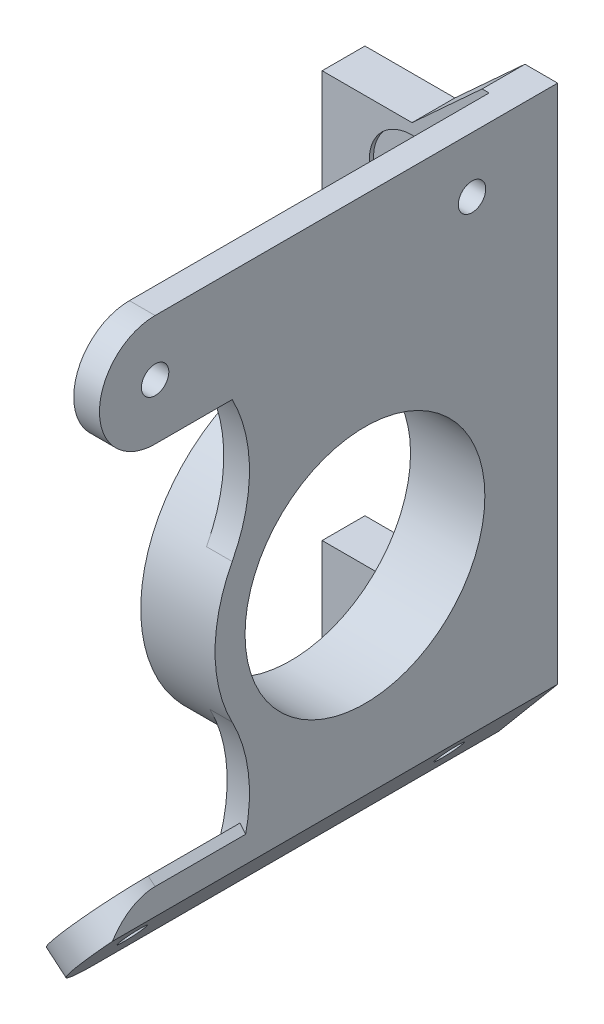
SolidWorks part; units mm, degrees
ref_plane "前视基准面" through (0, 0, 0) normal (0, 0, 1) x (1, 0, 0)
ref_plane "上视基准面" through (0, 0, 0) normal (0, 1, 0) x (1, 0, 0)
ref_plane "右视基准面" through (0, 0, 0) normal (1, 0, 0) x (0, 0, -1)
sketch "草图2" plane through (0, 0, 0) normal (0, 0, 1) x (1, 0, 0)
  line L0 (-14.7736, 24.3382) -> (-14.7736, -35.6618)
  line L1 (-14.7736, -35.6618) -> (30.2264, -35.6618)
  line L2 (7.7264, -35.6618) -> (7.7264, -23.1618)
  line L3 (21.55, -23.1618) -> (-6.0971, -23.1618)
  line L4 (-6.0971, -23.1618) -> (-6.0971, 11.8382)
  line L5 (-6.0971, 11.8382) -> (21.55, 11.8382)
  line L6 (7.7264, 11.8382) -> (7.7264, 24.3382)
  line L7 (30.2264, 24.3382) -> (-14.7736, 24.3382)
  line L8 (7.7264, 28.8603) -> (7.7264, -39.8897) construction
  line L9 (21.55, -23.1618) -> (21.55, 11.8382)
  line L10 (30.2264, 24.3382) -> (30.2264, -35.6618)
  line L11 (-18.1559, -5.6618) -> (33.2411, -5.6618) construction
  point P16 (-6.0971, -5.6618)
  point P17 (-14.7736, -5.6618)
  dimension "D1" = 45
  dimension "D2" = 35
  dimension "D3" = 60
extrude "凸台-拉伸2" add sketch "草图2" along normal blind 5 contours L6 L7 L0 L1 L2 L3 L4 L5 | L10 L7 L6 L5 L9 L3 L2 L1
sketch "草图4" plane through (0, 0, 5) normal (0, 0, 1) x (1, 0, 0)
  line L0 (-18.165, -5.6618) -> (33.9165, -5.6618) construction
  line L1 (-14.7736, 24.3382) -> (-14.7736, -35.6618) construction
  line L2 (-14.7736, -23.1618) -> (-6.0971, -23.1618)
  line L3 (-14.7736, -23.1618) -> (-14.7736, 11.8382)
  line L4 (-14.7736, 11.8382) -> (-6.0971, 11.8382)
  line L5 (-6.0971, -23.1618) -> (-6.0971, 11.8382)
  line L6 (-6.0971, -23.1618) -> (-6.0971, 11.8382) construction
  line L7 (7.7264, -39.813) -> (7.7264, 28.1228) construction
  line L8 (30.2264, 11.8382) -> (21.55, 11.8382)
  line L9 (21.55, -23.1618) -> (21.55, 11.8382)
  line L10 (30.2264, -23.1618) -> (21.55, -23.1618)
  line L11 (30.2264, -23.1618) -> (30.2264, 11.8382)
  point P17 (-14.7736, -5.6618)
  dimension "D1" = 35
extrude "凸台-拉伸15" add sketch "草图4" along normal blind 35
sketch "草图5" plane through (-14.7736, 0, 0) normal (-1, 0, 0) x (0, 0, 1)
  line L0 (0, -5.6618) -> (40, -5.6618)
  line L1 (0, 24.3382) -> (0, -35.6618) construction
  line L2 (40, 11.8382) -> (40, -23.1618) construction
  line L3 (22.5, 11.8382) -> (40, 11.8382)
  line L4 (40, 11.8382) -> (40, -23.1618)
  line L5 (40, -23.1618) -> (22.5, -23.1618)
  circle A0 centre (22.5, -5.6618) radius 17.5
  line M5 (5, -23.1618) -> (40, -23.1618)
  line M6 (40, -23.1618) -> (40, 11.8382)
  line M7 (40, 11.8382) -> (5, 11.8382)
  dimension "D1" = 35
extrude "切除-拉伸1" cut sketch "草图5" against normal blind 45 contours A0 M5 M6 | A0 M6 M7
sketch "草图6" plane through (-14.7736, 0, 0) normal (-1, 0, 0) x (0, 0, 1)
  circle A0 centre (22.5, -5.6618) radius 14
  dimension "D1" = 28
extrude "切除-拉伸2" cut sketch "草图6" against normal blind 45
fillet "圆角1" radius 5 4 edges at (-6.0971, 11.8382, 2.5) (21.55, 11.8382, 2.5) (-6.0971, -23.1618, 2.5) (21.55, -23.1618, 2.5)
sketch "草图7" plane through (-6.0971, 0, 0) normal (1, 0, 0) x (0, 0, -1)
  circle A0 centre (-22.5, -5.6618) radius 15
  circle A1 centre (-22.5, -5.6618) radius 13
extrude "凸台-拉伸16" add sketch "草图7" against normal blind 1
sketch "草图8" plane through (21.55, 0, 0) normal (-1, 0, 0) x (0, 0, 1)
  circle A0 centre (22.5, -5.6618) radius 15
  circle A1 centre (22.5, -5.6618) radius 10
sketch "草图9" plane through (0, 0, 5) normal (0, 0, 1) x (1, 0, 0)
  line L0 (7.7264, 24.3382) -> (7.7264, -35.6618)
  line L13 (30.2264, 24.3382) -> (-14.7736, 24.3382) construction
  line L14 (-14.7736, -35.6618) -> (30.2264, -35.6618) construction
sketch "草图11" plane through (0, 0, 5) normal (0, 0, 1) x (1, 0, 0)
  line L0 (-14.7736, 18.0882) -> (30.2264, 18.0882)
  line L1 (-14.7736, 24.3382) -> (-14.7736, 11.8382) construction
  line L2 (30.2264, 24.3382) -> (30.2264, 11.8382) construction
  line L3 (7.7264, 24.3382) -> (7.7264, -35.6618) construction
  line L4 (30.2264, 24.3382) -> (-14.7736, 24.3382) construction
  line L5 (-14.7736, -35.6618) -> (30.2264, -35.6618) construction
  line L6 (7.7264, -5.6618) -> (45.6912, -5.6618) construction
  line L7 (45.6912, -5.6618) -> (45.6912, 4.9969) construction
  line L10 (-14.7736, -29.4118) -> (30.2264, -29.4118)
  line L11 (-14.7736, -23.1618) -> (-14.7736, -35.6618) construction
  point P4 (-2.7736, 18.0882)
  point P16 (-2.7736, -29.4118)
  point P18 (18.2264, -29.4118)
  point P25 (18.2264, 18.0882)
  dimension "D1" = 12
split "分割1" trim tools "草图9" bodies to split 111 resulting bodies 117 118
delete or keep bodies "实体-删除/保留 2" type delete bodies bodies 117
hole_wizard "打孔尺寸(%根据六角头螺)栓 全螺纹的类型1" positions "3D草图2" profile "草图31" counterbore size "M4" standard "GB"
sketch3d "3D草图2"
  point P0 (18.2264, 18.0882, 5)
  point P3 (18.2264, -29.4118, 5)
sketch "草图31" plane through (18.2264, 18.0882, 5) normal (1, 0, 0) x (0, -1, 0)
  line L0 (0, 0) -> (0, 6.2919)
  line L1 (0, 6.2919) -> (2.15, 5)
  line L2 (2.15, 5) -> (2.15, 0.5)
  line L3 (2.15, 0.5) -> (5, 0.5)
  line L4 (5, 0.5) -> (5, 0)
  line L5 (5, 0) -> (0, 0)
  line L10 (0, 6.2919) -> (-2.15, 5) construction
  line L11 (0, -6.35) -> (0, 107.95) construction
  dimension "孔直径" = 4.3
  dimension "孔深度" = 5
  dimension "柱形沉头孔直径" = 10
  dimension "柱形沉头孔深度" = 0.5
  dimension "导头角度" = 118
sketch "草图17" plane through (0, 0, 5) normal (0, 0, 1) x (1, 0, 0)
  line L5 (30.2264, 31.8382) -> (27.2264, 31.8382)
  line L6 (30.2264, 31.8382) -> (30.2264, 18.8382)
  line L7 (30.2264, 18.8382) -> (27.2264, 18.8382)
  line L8 (27.2264, 31.8382) -> (27.2264, 18.8382)
  line L9 (30.2264, 24.3382) -> (30.2264, 11.8382) construction
  line L10 (30.2264, 11.8382) -> (21.55, 11.8382) construction
  dimension "D1" = 3
  dimension "D4" = 13
  dimension "D6" = 7
extrude "凸台-拉伸20" add sketch "草图17" along normal blind 42
sketch "草图18" plane through (30.2264, 0, 0) normal (1, 0, 0) x (0, 0, -1)
  line L3 (-47, 18.8382) -> (-47, 31.8382)
  arc A0 (-47, 31.8382) -> (-47, 18.8382) centre (-47, 25.3382) ccw
extrude "凸台-拉伸21" add sketch "草图18" against normal blind 3
sketch "草图19" plane through (30.2264, 0, 0) normal (1, 0, 0) x (0, 0, -1)
  circle A0 centre (-47, 25.3382) radius 1.6
  circle A2 centre (-10, 25.3382) radius 1.6
  dimension "D1" = 37
extrude "切除-拉伸3" cut sketch "草图19" against normal blind 3
sketch "草图24" plane through (30.2264, 0, 0) normal (1, 0, 0) x (0, 0, -1)
  line L11 (-5, 18.8382) -> (-38, 18.8382)
  line L12 (-5, 18.8382) -> (-5, 11.8382)
  line L14 (-38, 18.8382) -> (-38, 2.4623) construction
  line L15 (-22.5, 11.8382) -> (-5, 11.8382) construction
  line L16 (-22.5, 11.8382) -> (-5, 11.8382)
  line L19 (-5, 11.8382) -> (-5, -23.1618) construction
  line L21 (-38, 2.4623) -> (-38, -13.7858) construction
  arc A2 (-22.5, 11.8382) -> (-22.5, -23.1618) centre (-22.5, -5.6618) ccw construction
  arc A3 (-22.5, 11.8382) -> (-38, 2.4623) centre (-22.5, -5.6618) ccw
  arc A4 (-38, 2.4623) -> (-38, -13.7858) centre (-22.5, -5.6618) ccw construction
  arc A6 (-38, 2.4623) -> (-38, 18.8382) centre (-53.622, 10.6503) ccw
  dimension "D1" = 33
extrude "凸台-拉伸25" add sketch "草图24" against normal blind 3
sketch "草图21" plane through (0, 0, 5) normal (0, 0, 1) x (1, 0, 0)
  line L1 (30.2264, 18.8382) -> (30.2264, 31.8382) construction
  line L5 (18.2264, 24.3382) -> (30.2264, 24.3382)
  line L6 (27.2264, 24.3382) -> (7.7264, 24.3382) construction
  line L8 (30.2264, 24.3382) -> (30.2264, 31.8382)
  line L9 (26.4082, 31.8382) -> (18.2264, 24.3382)
  line L15 (30.2264, 31.8382) -> (26.4082, 31.8382)
  line L16 (30.2264, 31.8382) -> (30.2264, 35.3382) construction
  line L17 (30.2264, 35.3382) -> (26.4082, 31.8382) construction
  dimension "D3" = 12
  dimension "D4" = 11
extrude "凸台-拉伸22" add sketch "草图21" against normal blind 5
sketch "草图34" plane through (0, 0, 5) normal (0, 0, 1) x (1, 0, 0)
  line L0 (30.2264, -23.1618) -> (30.2264, -35.6618) construction
  line L1 (21.0721, -35.192) -> (23.3702, -37.1203)
  line L2 (21.0721, -35.192) -> (29.4283, -25.2334)
  line L3 (29.4283, -25.2334) -> (30.2264, -25.9031)
  line L4 (23.3702, -37.1203) -> (30.2264, -28.9494)
  line L5 (21.0721, -35.192) -> (31.7264, -27.1618) construction
  line L6 (29.4283, -25.2334) -> (23.3702, -37.1203) construction
  line L7 (21.55, -23.1618) -> (30.2264, -23.1618) construction
  line L8 (30.2264, -25.9031) -> (30.2264, -28.9494)
  line L9 (30.2264, -28.9494) -> (31.7264, -27.1618) construction
  line L10 (30.2264, -25.9031) -> (31.7264, -27.1618) construction
  point P0 (26.3992, -31.1769)
  dimension "D1" = 3
  dimension "D2" = 13
  dimension "D3" = 40
  dimension "D4" = 4
  dimension "D5" = 1.5
extrude "凸台-拉伸26" add sketch "草图34" along normal blind 42
sketch "草图37" plane through (30.2264, 0, 0) normal (1, 0, 0) x (0, 0, -1)
  line L0 (-40, -5.6618) -> (-5, -5.6618) construction
  line L1 (-5, 24.3382) -> (-5, -35.6618) construction
  line L3 (-37.4223, -28.9494) -> (-5, -28.9494)
  line L4 (-5, -28.9494) -> (-5, -23.1618)
  line L5 (-22.5, -23.1618) -> (-5, -23.1618) construction
  line L6 (-22.5, -23.1618) -> (-5, -23.1618)
  arc A0 (-38, 2.4623) -> (-22.5, -23.1618) centre (-22.5, -5.6618) ccw construction
  arc A1 (-38, 2.4623) -> (-38, 18.8382) centre (-53.622, 10.6503) ccw construction
  arc A2 (-38, 2.4623) -> (-38, 18.8382) centre (-53.622, 10.6503) ccw construction
  arc A3 (-38, -13.7858) -> (-37.4223, -28.9494) centre (-53.622, -21.9738) cw
  arc A5 (-38, -13.7858) -> (-22.5, -23.1618) centre (-22.5, -5.6618) ccw
extrude "凸台-拉伸27" add sketch "草图37" against normal blind 2.6
sketch "草图38" plane through (0, 0, 5) normal (0, 0, 1) x (1, 0, 0)
  line L3 (30.2264, -35.6618) -> (30.2264, -28.9494)
  line L4 (30.2264, -28.9494) -> (24.5941, -35.6618)
  line L5 (24.5941, -35.6618) -> (30.2264, -35.6618)
  line L6 (30.2264, -35.6618) -> (30.2264, -28.9494)
  line L7 (30.2264, -28.9494) -> (24.5941, -35.6618)
  line L8 (24.5941, -35.6618) -> (30.2264, -35.6618)
  dimension "D1" = 0
extrude "切除-拉伸5" cut sketch "草图38" against normal blind 22.6
sketch "草图39" plane through (0, 0, 5) normal (0, 0, 1) x (1, 0, 0)
  line L4 (24.5941, -35.6618) -> (21.6319, -35.6618)
  line L5 (23.3702, -37.1203) -> (24.5941, -35.6618)
  line L6 (21.6319, -35.6618) -> (23.3702, -37.1203)
  line L8 (24.5941, -35.6618) -> (21.6319, -35.6618)
  line L9 (23.3702, -37.1203) -> (24.5941, -35.6618)
  line L10 (21.6319, -35.6618) -> (23.3702, -37.1203)
  point P2 (0, 0)
  point P8 (0, 0)
  point P9 (0, 0)
  point P10 (0, 0)
  dimension "D1" = 0
sketch "草图41" plane through (31.9924, -26.8448, 0) normal (0.766, -0.6428, 0) x (0, 0, -1)
  line L1 (-47, -13.4138) -> (-47, -0.4138)
  line L2 (-47, -13.4138) -> (-47, -2.7474) construction
  line L3 (-47, -13.4138) -> (-5, -13.4138) construction
  arc A0 (-47, -0.4138) -> (-47, -13.4138) centre (-47, -6.9138) ccw
  line M5 (-47, -2.7474) -> (-47, -13.4138)
extrude "凸台-拉伸29" add sketch "草图41" against normal up to surface (3 mm away) contours A0 M5 up to face at (26.0411, -29.2702, 29.5146)
sketch "草图42" plane through (31.9924, -26.8448, 0) normal (0.766, -0.6428, 0) x (0, 0, -1)
  line L0 (-47, -6.9138) -> (-10, -6.9138) construction
  circle A0 centre (-47, -6.9138) radius 1.5
  circle A1 centre (-10, -6.9138) radius 1.5
  dimension "D1" = 3
  dimension "D2" = 37
extrude "切除-拉伸6" cut sketch "草图42" against normal through all
sketch "草图44" plane through (0, 0, 47) normal (0, 0, -1) x (-1, 0, 0)
  line L3 (-31.7264, -27.1618) -> (-30.2264, -28.9494)
  line L4 (-30.2264, -28.9494) -> (-30.2264, -25.9031)
  line L5 (-30.2264, -25.9031) -> (-31.7264, -27.1618)
  line L6 (-31.7264, -27.1618) -> (-30.2264, -28.9494)
  line L7 (-30.2264, -28.9494) -> (-30.2264, -25.9031)
  line L8 (-30.2264, -25.9031) -> (-31.7264, -27.1618)
  dimension "D1" = 0
extrude "切除-拉伸7" cut sketch "草图44" against normal blind 8.6
extrude "凸台-拉伸31" add sketch "草图39" against normal up to surface (5 mm away) up to face at (20.3764, 18.0882, 0)
move or copy body "实体-移动/复制2" [suppressed] bodies to move or copy 155
move or copy body "实体-移动/复制1" [suppressed]
